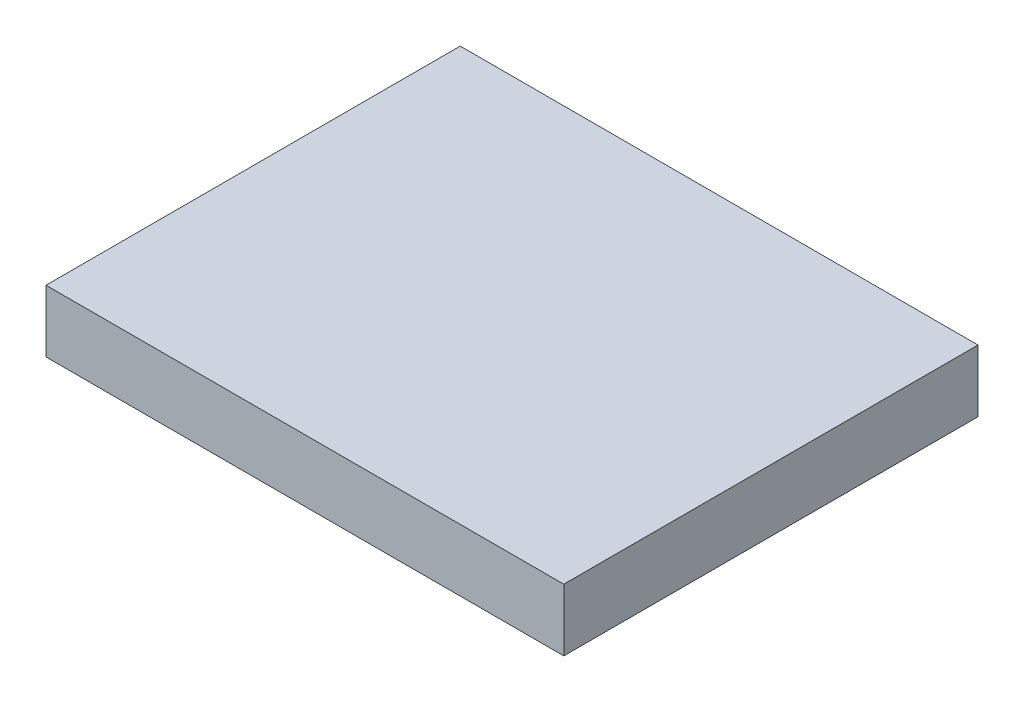
SolidWorks part; units mm, degrees
ref_plane "Front Plane" through (0, 0, 0) normal (0, 0, 1) x (1, 0, 0)
ref_plane "Top Plane" through (0, 0, 0) normal (0, 1, 0) x (1, 0, 0)
ref_plane "Right Plane" through (0, 0, 0) normal (1, 0, 0) x (0, 0, -1)
sketch "Sketch1" plane through (0, 0, 0) normal (0, 1, 0) x (1, 0, 0)
  line L1 (-12.5, 10) -> (12.5, 10)
  line L2 (-12.5, 10) -> (-12.5, -10)
  line L3 (-12.5, -10) -> (12.5, -10)
  line L4 (12.5, 10) -> (12.5, -10)
  line L5 (-12.5, 10) -> (12.5, -10) construction
  line L6 (-12.5, -10) -> (12.5, 10) construction
  point P0 (0, 0)
  dimension "D1" = 20
  dimension "D2" = 25
extrude "Boss-Extrude1" add sketch "Sketch1" along normal blind 3
